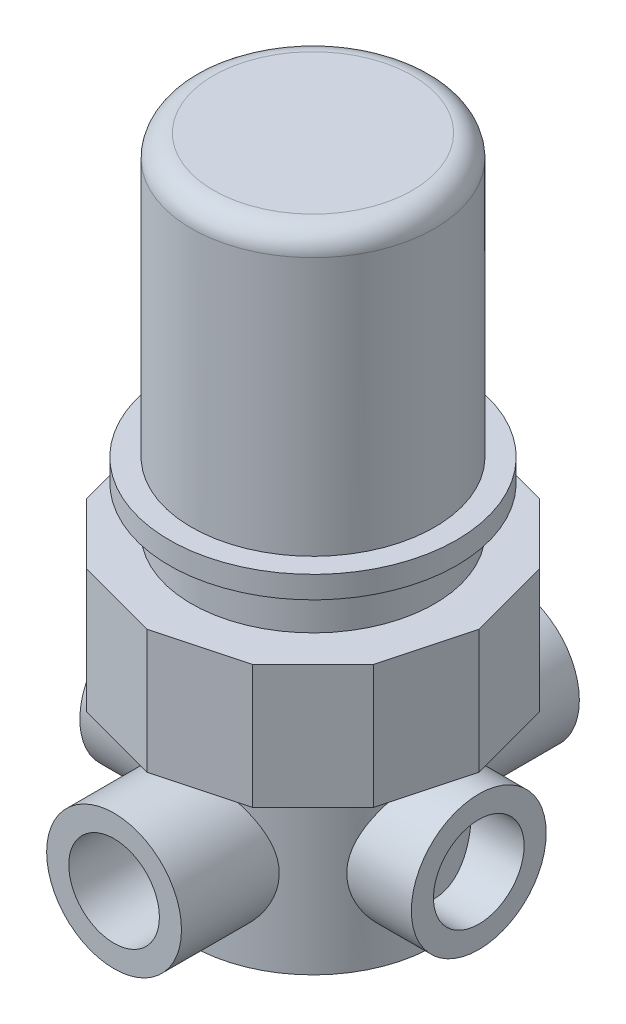
SolidWorks part; units mm, degrees
ref_plane "Front Plane" through (0, 0, 0) normal (0, 0, 1) x (1, 0, 0)
ref_plane "Top Plane" through (0, 0, 0) normal (0, 1, 0) x (1, 0, 0)
ref_plane "Right Plane" through (0, 0, 0) normal (1, 0, 0) x (0, 0, -1)
sketch "Sketch1" plane through (0, 0, 0) normal (0, 0, 1) x (1, 0, 0)
  line L0 (0, 73.914) -> (0, 0) construction
  line L1 (0, 73.914) -> (13.97, 73.914)
  line L2 (13.97, 73.914) -> (13.97, 41.656)
  line L3 (13.97, 41.656) -> (16.51, 41.656)
  line L4 (16.51, 41.656) -> (16.51, 39.116)
  line L5 (16.51, 39.116) -> (13.97, 39.116)
  line L6 (13.97, 39.116) -> (13.97, 34.036)
  line L7 (13.97, 34.036) -> (19.05, 34.036)
  line L8 (19.05, 34.036) -> (19.05, 19.812)
  line L9 (19.05, 19.812) -> (13.97, 19.812)
  line L10 (13.97, 19.812) -> (13.97, 0)
  line L11 (13.97, 0) -> (0, 0)
  line L12 (0, 73.914) -> (0, 0)
  dimension "D1" = 27.94
  dimension "D2" = 38.1
  dimension "D3" = 2.54
  dimension "D4" = 5.08
  dimension "D5" = 19.812
  dimension "D6" = 14.224
  dimension "D7" = 73.914
revolve "Revolve1" add sketch "Sketch1" angle 360 about L0
sketch "Sketch2" plane through (0, 34.036, 0) normal (0, 1, 0) x (1, 0, 0)
  line L1 (0, 19.05) -> (-9.525, 16.4978)
  line L2 (-9.525, 16.4978) -> (-16.4978, 9.525)
  line L3 (-16.4978, 9.525) -> (-19.05, 0)
  line L4 (-19.05, 0) -> (-16.4978, -9.525)
  line L5 (-16.4978, -9.525) -> (-9.525, -16.4978)
  line L6 (-9.525, -16.4978) -> (0, -19.05)
  line L7 (0, -19.05) -> (9.525, -16.4978)
  line L8 (9.525, -16.4978) -> (16.4978, -9.525)
  line L9 (16.4978, -9.525) -> (19.05, 0)
  line L10 (19.05, 0) -> (16.4978, 9.525)
  line L11 (16.4978, 9.525) -> (9.525, 16.4978)
  line L12 (9.525, 16.4978) -> (0, 19.05)
  circle A0 centre (0, 0) radius 18.4009 construction
  circle A1 centre (0, 0) radius 19.05 construction
  circle A3 centre (0, 0) radius 19.05
  circle M2 centre (0, 0) radius 19.05
extrude "Cut-Extrude1" cut sketch "Sketch2" against normal up to next contours L2 M2 | L3 M2 | L4 M2 | L5 M2 | L6 M2 | L7 M2 | L8 M2 | L9 M2 | L10 M2 | L11 M2 | L12 M2 | L1 M2 | A3
ref_plane "Plane1" through (0, 0, 13.97) normal (0, 0, 1) x (1, 0, 0)
sketch "Sketch3" plane through (0, 0, 13.97) normal (0, 0, 1) x (1, 0, 0)
  line L0 (0, 19.812) -> (0, 0) construction
  circle A0 centre (0, 9.906) radius 5.207
  circle A1 centre (0, 9.906) radius 7.747
  dimension "D1" = 10.414
  dimension "D2" = 2.54
extrude "Boss-Extrude1" add sketch "Sketch3" along normal blind 8.89 and the other way up to next (8.89 mm away)
pattern_circular "CirPattern1" count 4 over 360 about axis through (0, 0, 0) along (0, 1, 0) of "Boss-Extrude1"
sketch "Sketch4" plane through (22.86, 0, 0) normal (1, 0, 0) x (0, 0, -1)
  circle A1 centre (0, 9.906) radius 7.747
  circle A2 centre (0, 9.906) radius 7.747
  dimension "D1" = 0
extrude "Cut-Extrude2" cut sketch "Sketch4" against normal blind 3.81
mirror "Mirror2" about plane through (0, 0, 0) normal (1, 0, 0) of "Cut-Extrude2"
fillet "Fillet1" radius 2.54 1 edges at (-13.97, 73.914, 0)
